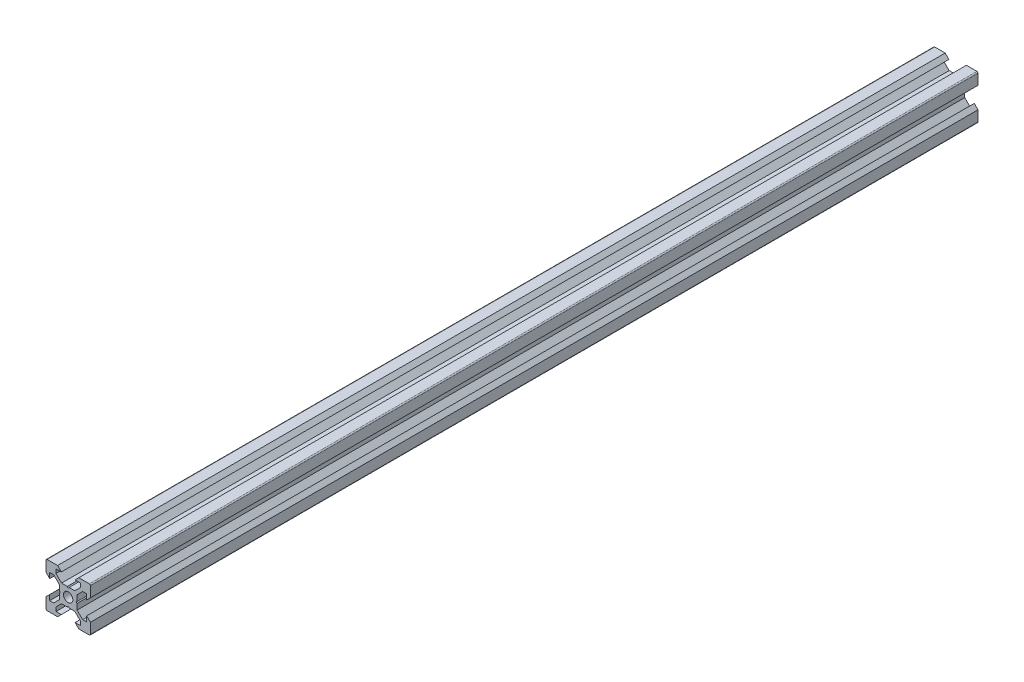
SolidWorks part; units mm, degrees
ref_plane "Front Plane" through (0, 0, 0) normal (0, 0, 1) x (1, 0, 0)
ref_plane "Top Plane" through (0, 0, 0) normal (0, 1, 0) x (1, 0, 0)
ref_plane "Right Plane" through (0, 0, 0) normal (1, 0, 0) x (0, 0, -1)
sketch "Sketch1" plane through (0, 0, 0) normal (0, 0, 1) x (1, 0, 0)
  line L0 (0, 11.7715) -> (0, -11.0375) construction
  line L1 (-10, 10) -> (10, 10) construction
  line L2 (-10, 10) -> (-10, -10) construction
  line L3 (-10, -10) -> (10, -10) construction
  line L4 (10, 10) -> (10, -10) construction
  line L5 (-10, 10) -> (10, -10) construction
  line L6 (-10, -10) -> (10, 10) construction
  line L7 (-5.5, 5.5) -> (5.5, 5.5) construction
  line L8 (-5.5, 5.5) -> (-5.5, -5.5) construction
  line L9 (-5.5, -5.5) -> (5.5, -5.5) construction
  line L10 (5.5, 5.5) -> (5.5, -5.5) construction
  line L11 (-5.5, 5.5) -> (5.5, -5.5) construction
  line L12 (-5.5, -5.5) -> (5.5, 5.5) construction
  line L13 (-10, 10) -> (-4.775, 10)
  line L14 (-4.775, 10) -> (-3.1, 8.325)
  line L15 (-3.1, 8.325) -> (-5.5, 8.325)
  line L16 (-5.5, 8.325) -> (-5.5, 6.525)
  line L17 (-5.5, 6.525) -> (-3, 4.025)
  line L18 (-3, 4.025) -> (3, 4.025)
  line L19 (-2.8044, 0) -> (3.0922, 0) construction
  line L20 (5.5, 6.525) -> (3, 4.025)
  line L21 (5.5, 8.325) -> (5.5, 6.525)
  line L22 (3.1, 8.325) -> (5.5, 8.325)
  line L23 (4.775, 10) -> (3.1, 8.325)
  line L24 (10, 10) -> (4.775, 10)
  line L25 (10, -10) -> (4.775, -10)
  line L26 (4.775, -10) -> (3.1, -8.325)
  line L27 (3.1, -8.325) -> (5.5, -8.325)
  line L28 (5.5, -8.325) -> (5.5, -6.525)
  line L29 (5.5, -6.525) -> (3, -4.025)
  line L30 (-3.1, -8.325) -> (-5.5, -8.325)
  line L31 (-3, -4.025) -> (3, -4.025)
  line L32 (-5.5, -6.525) -> (-3, -4.025)
  line L33 (-5.5, -8.325) -> (-5.5, -6.525)
  line L34 (-4.775, -10) -> (-3.1, -8.325)
  line L35 (-10, -10) -> (-4.775, -10)
  line L36 (-4.025, 3) -> (-4.025, -3)
  line L37 (-6.525, 5.5) -> (-4.025, 3)
  line L38 (-8.325, 5.5) -> (-6.525, 5.5)
  line L39 (-8.325, 3.1) -> (-8.325, 5.5)
  line L40 (-10, 4.775) -> (-8.325, 3.1)
  line L41 (-10, 10) -> (-10, 4.775)
  line L42 (-10, -10) -> (-10, -4.775)
  line L43 (-10, -4.775) -> (-8.325, -3.1)
  line L44 (-8.325, -3.1) -> (-8.325, -5.5)
  line L45 (-8.325, -5.5) -> (-6.525, -5.5)
  line L46 (-6.525, -5.5) -> (-4.025, -3)
  line L47 (10, -10) -> (10, -4.775)
  line L48 (10, -4.775) -> (8.325, -3.1)
  line L49 (8.325, -3.1) -> (8.325, -5.5)
  line L50 (8.325, -5.5) -> (6.525, -5.5)
  line L51 (6.525, -5.5) -> (4.025, -3)
  line L52 (4.025, 3) -> (4.025, -3)
  line L53 (6.525, 5.5) -> (4.025, 3)
  line L54 (8.325, 5.5) -> (6.525, 5.5)
  line L55 (8.325, 3.1) -> (8.325, 5.5)
  line L56 (10, 4.775) -> (8.325, 3.1)
  line L57 (10, 10) -> (10, 4.775)
  circle A0 centre (0, 0) radius 2.1
  point P0 (0, 0)
  point P6 (0, 0)
  point P23 (0, 4.025)
  dimension "D3" = 4.2
  dimension "D1" = 20
  dimension "D2" = 20
  dimension "D4" = 45
  dimension "D5" = 45
  dimension "D6" = 9.55
  dimension "D7" = 6.2
  dimension "D8" = 11
  dimension "D9" = 1.675
  dimension "D10" = 4.3
  dimension "D11" = 9.55
  dimension "D12" = 6.2
  dimension "D13" = 1.675
  dimension "D14" = 4.3
  dimension "D15" = 1.8
  dimension "D16" = 1.8
  dimension "D17" = 45
extrude "Boss-Extrude1" add sketch "Sketch1" along normal blind 400
fillet "Fillet1" radius 0.5 4 edges at (-10, -10, 200) (10, -10, 200) (10, 10, 200) (-10, 10, 200)
sketch "Sketch2" plane through (0, 0, 400) normal (0, 0, 1) x (1, 0, 0)
  line L0 (-0.8203, 0) -> (1.3478, 0) construction
  line L1 (0, 1.2196) -> (0, -1.1398) construction
  line L44 (-10, -4.775) -> (-10, -9.5)
  line L45 (-9.5, -10) -> (-4.775, -10)
  line L46 (-4.775, -10) -> (-3.1, -8.325)
  line L47 (-3.1, -8.325) -> (-5.5, -8.325)
  line L48 (-5.5, -8.325) -> (-5.5, -6.525)
  line L49 (-5.5, -6.525) -> (-3, -4.025)
  line L50 (-3, -4.025) -> (3, -4.025)
  line L51 (3, -4.025) -> (5.5, -6.525)
  line L52 (5.5, -6.525) -> (5.5, -8.325)
  line L53 (5.5, -8.325) -> (3.1, -8.325)
  line L54 (3.1, -8.325) -> (4.775, -10)
  line L55 (4.775, -10) -> (9.5, -10)
  line L56 (10, -9.5) -> (10, -4.775)
  line L57 (10, -4.775) -> (8.325, -3.1)
  line L58 (8.325, -3.1) -> (8.325, -5.5)
  line L59 (8.325, -5.5) -> (6.525, -5.5)
  line L60 (6.525, -5.5) -> (4.025, -3)
  line L61 (4.025, -3) -> (4.025, 3)
  line L62 (4.025, 3) -> (6.525, 5.5)
  line L63 (6.525, 5.5) -> (8.325, 5.5)
  line L64 (8.325, 5.5) -> (8.325, 3.1)
  line L65 (8.325, 3.1) -> (10, 4.775)
  line L66 (10, 4.775) -> (10, 9.5)
  line L67 (9.5, 10) -> (4.775, 10)
  line L68 (4.775, 10) -> (3.1, 8.325)
  line L69 (3.1, 8.325) -> (5.5, 8.325)
  line L70 (5.5, 8.325) -> (5.5, 6.525)
  line L71 (5.5, 6.525) -> (3, 4.025)
  line L72 (3, 4.025) -> (-3, 4.025)
  line L73 (-3, 4.025) -> (-5.5, 6.525)
  line L74 (-5.5, 6.525) -> (-5.5, 8.325)
  line L75 (-5.5, 8.325) -> (-3.1, 8.325)
  line L76 (-3.1, 8.325) -> (-4.775, 10)
  line L77 (-4.775, 10) -> (-9.5, 10)
  line L78 (-10, 9.5) -> (-10, 4.775)
  line L79 (-10, 4.775) -> (-8.325, 3.1)
  line L80 (-8.325, 3.1) -> (-8.325, 5.5)
  line L81 (-8.325, 5.5) -> (-6.525, 5.5)
  line L82 (-6.525, 5.5) -> (-4.025, 3)
  line L83 (-4.025, 3) -> (-4.025, -3)
  line L84 (-4.025, -3) -> (-6.525, -5.5)
  line L85 (-6.525, -5.5) -> (-8.325, -5.5)
  line L86 (-8.325, -5.5) -> (-8.325, -3.1)
  line L87 (-8.325, -3.1) -> (-10, -4.775)
  line L88 (-10, -4.775) -> (-10, -9.5)
  line L89 (-9.5, -10) -> (-4.775, -10)
  line L90 (-4.775, -10) -> (-3.1, -8.325)
  line L91 (-3.1, -8.325) -> (-5.5, -8.325)
  line L92 (-5.5, -8.325) -> (-5.5, -6.525)
  line L93 (-5.5, -6.525) -> (-3, -4.025)
  line L94 (-3, -4.025) -> (3, -4.025)
  line L95 (3, -4.025) -> (5.5, -6.525)
  line L96 (5.5, -6.525) -> (5.5, -8.325)
  line L97 (5.5, -8.325) -> (3.1, -8.325)
  line L98 (3.1, -8.325) -> (4.775, -10)
  line L99 (4.775, -10) -> (9.5, -10)
  line L100 (10, -9.5) -> (10, -4.775)
  line L101 (10, -4.775) -> (8.325, -3.1)
  line L102 (8.325, -3.1) -> (8.325, -5.5)
  line L103 (8.325, -5.5) -> (6.525, -5.5)
  line L104 (6.525, -5.5) -> (4.025, -3)
  line L105 (4.025, -3) -> (4.025, 3)
  line L106 (4.025, 3) -> (6.525, 5.5)
  line L107 (6.525, 5.5) -> (8.325, 5.5)
  line L108 (8.325, 5.5) -> (8.325, 3.1)
  line L109 (8.325, 3.1) -> (10, 4.775)
  line L110 (10, 4.775) -> (10, 9.5)
  line L111 (9.5, 10) -> (4.775, 10)
  line L112 (4.775, 10) -> (3.1, 8.325)
  line L113 (3.1, 8.325) -> (5.5, 8.325)
  line L114 (5.5, 8.325) -> (5.5, 6.525)
  line L115 (5.5, 6.525) -> (3, 4.025)
  line L116 (3, 4.025) -> (-3, 4.025)
  line L117 (-3, 4.025) -> (-5.5, 6.525)
  line L118 (-5.5, 6.525) -> (-5.5, 8.325)
  line L119 (-5.5, 8.325) -> (-3.1, 8.325)
  line L120 (-3.1, 8.325) -> (-4.775, 10)
  line L121 (-4.775, 10) -> (-9.5, 10)
  line L122 (-10, 9.5) -> (-10, 4.775)
  line L123 (-10, 4.775) -> (-8.325, 3.1)
  line L124 (-8.325, 3.1) -> (-8.325, 5.5)
  line L125 (-8.325, 5.5) -> (-6.525, 5.5)
  line L126 (-6.525, 5.5) -> (-4.025, 3)
  line L127 (-4.025, 3) -> (-4.025, -3)
  line L128 (-4.025, -3) -> (-6.525, -5.5)
  line L129 (-6.525, -5.5) -> (-8.325, -5.5)
  line L130 (-8.325, -5.5) -> (-8.325, -3.1)
  line L131 (-8.325, -3.1) -> (-10, -4.775)
  circle A0 centre (-4.025, 0) radius 0.4
  circle A1 centre (4.025, 0) radius 0.4
  circle A2 centre (0, 4.025) radius 0.4
  circle A3 centre (0, -4.025) radius 0.4
  arc A4 (-10, -9.5) -> (-9.5, -10) centre (-9.5, -9.5) ccw
  arc A5 (9.5, -10) -> (10, -9.5) centre (9.5, -9.5) ccw
  arc A6 (10, 9.5) -> (9.5, 10) centre (9.5, 9.5) ccw
  arc A7 (-9.5, 10) -> (-10, 9.5) centre (-9.5, 9.5) ccw
  arc A8 (-10, -9.5) -> (-9.5, -10) centre (-9.5, -9.5) ccw
  arc A9 (9.5, -10) -> (10, -9.5) centre (9.5, -9.5) ccw
  arc A10 (10, 9.5) -> (9.5, 10) centre (9.5, 9.5) ccw
  arc A11 (-9.5, 10) -> (-10, 9.5) centre (-9.5, 9.5) ccw
  dimension "D2" = 0.8
  dimension "D3" = 0.8
  dimension "D1" = 0
extrude "Cut-Extrude1" cut sketch "Sketch2" against normal through all contours L127 A0 | L116 A2 | A1 L105 | A3 L94
